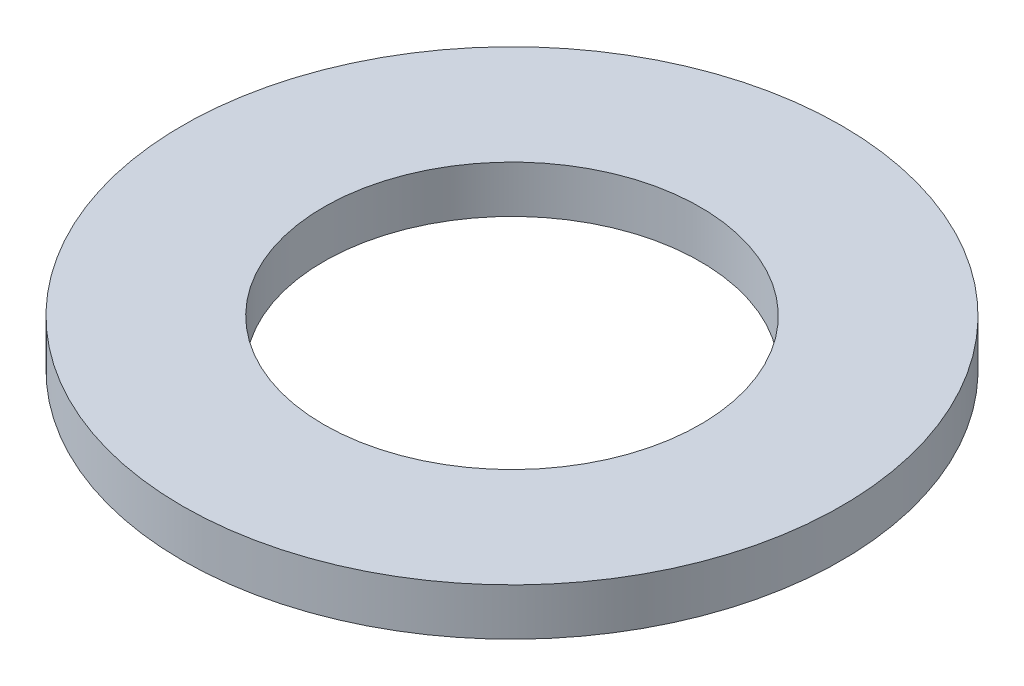
SolidWorks part; units mm, degrees
ref_plane "Front Plane" through (0, 0, 0) normal (0, 0, 1) x (1, 0, 0)
ref_plane "Top Plane" through (0, 0, 0) normal (0, 1, 0) x (1, 0, 0)
ref_plane "Right Plane" through (0, 0, 0) normal (1, 0, 0) x (0, 0, -1)
sketch "Sketch1" plane through (0, 0, 0) normal (0, 1, 0) x (1, 0, 0)
  circle A0 centre (0, 0) radius 7
  dimension "OD" = 14
extrude "Boss-Extrude1" add sketch "Sketch1" along normal blind 1
sketch "Sketch5" plane through (0, 1, 0) normal (0, 1, 0) x (-1, 0, 0)
  circle A0 centre (0, 0) radius 4
  dimension "ID" = 8
extrude "Cut-Extrude1" cut sketch "Sketch5" against normal through all
